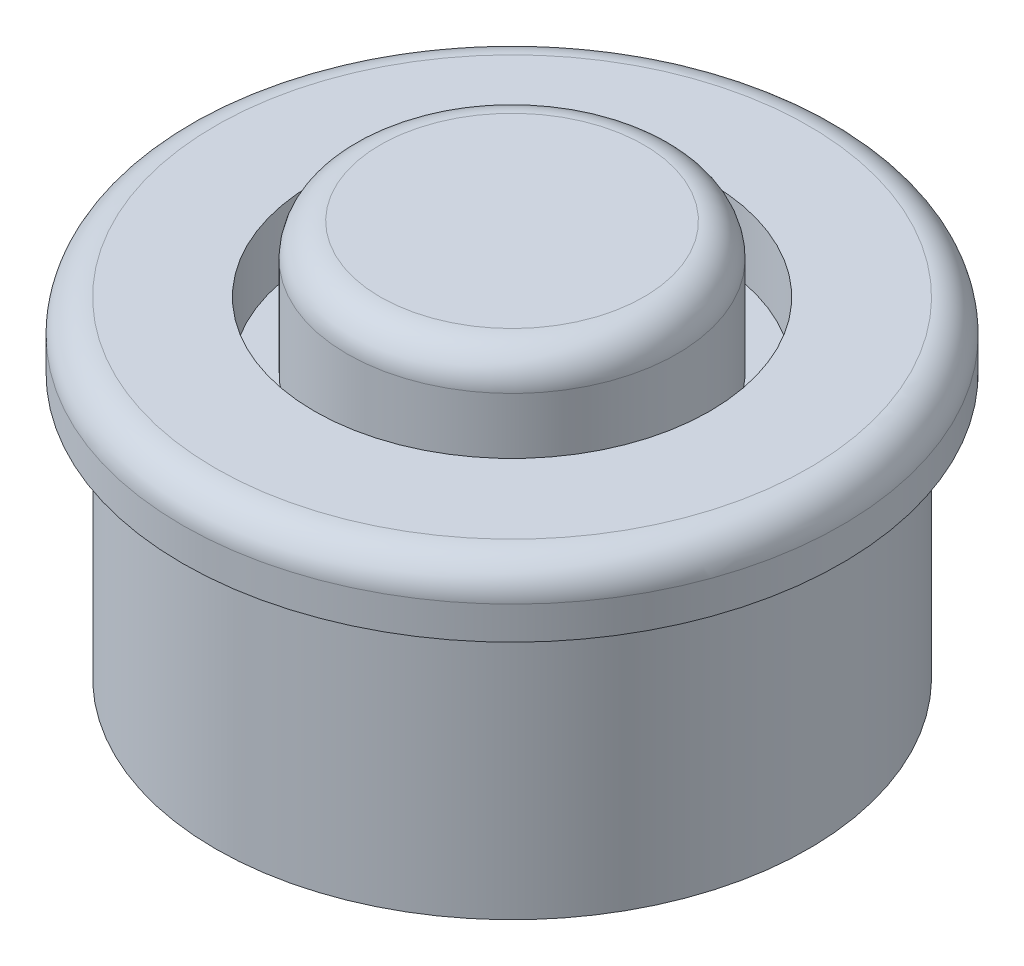
SolidWorks part; units mm, degrees
ref_plane "Front Plane" through (0, 0, 0) normal (0, 0, 1) x (1, 0, 0)
ref_plane "Top Plane" through (0, 0, 0) normal (0, 1, 0) x (1, 0, 0)
ref_plane "Right Plane" through (0, 0, 0) normal (1, 0, 0) x (0, 0, -1)
sketch "Sketch1" plane through (0, 0, 0) normal (0, 1, 0) x (1, 0, 0)
  circle A4 centre (0, 0) radius 6
  circle A5 centre (0, 0) radius 10
  dimension "D4" = 12
  dimension "D1" = 20
extrude "Boss-Extrude1" add sketch "Sketch1" along normal blind 2
sketch "Sketch2" plane through (0, 0, 0) normal (0, 1, 0) x (1, 0, 0)
  circle A4 centre (0, 0) radius 9
  dimension "D1" = 18
extrude "Boss-Extrude2" add sketch "Sketch2" against normal blind 8
sketch "Sketch3" plane through (0, 0, 0) normal (0, 1, 0) x (1, 0, 0)
  circle A0 centre (0, 0) radius 5
  dimension "D1" = 10
extrude "Boss-Extrude3" add sketch "Sketch3" along normal blind 4
fillet "Fillet1" radius 1 2 edges at (0, 4, 5) (0, 2, 10)
